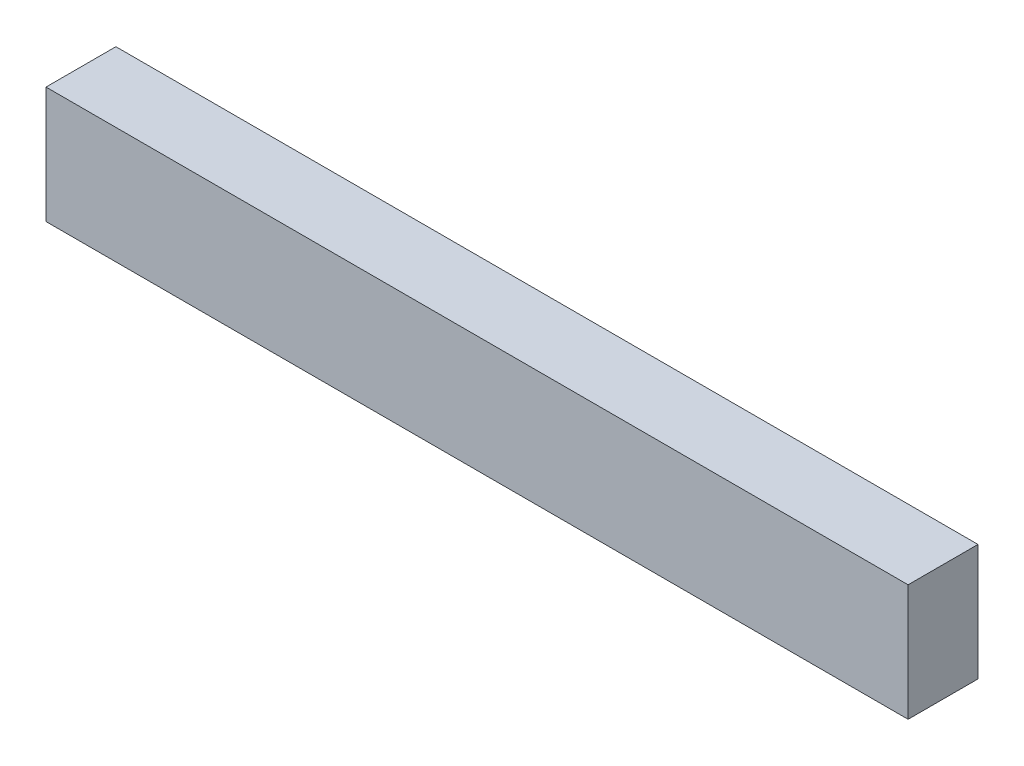
SolidWorks part; units mm, degrees
material "Pine"
ref_plane "Front Plane" through (0, 0, 0) normal (0, 0, 1) x (1, 0, 0)
ref_plane "Top Plane" through (0, 0, 0) normal (0, 1, 0) x (1, 0, 0)
ref_plane "Right Plane" through (0, 0, 0) normal (1, 0, 0) x (0, 0, -1)
sketch "Sketch1" plane through (0, 0, 0) normal (0, 1, 0) x (1, 0, 0)
  line L1 (-117.475, -9.525) -> (117.475, -9.525)
  line L2 (-117.475, -9.525) -> (-117.475, 9.525)
  line L3 (-117.475, 9.525) -> (117.475, 9.525)
  line L4 (117.475, -9.525) -> (117.475, 9.525)
  line L5 (-117.475, -9.525) -> (117.475, 9.525) construction
  line L6 (-117.475, 9.525) -> (117.475, -9.525) construction
  point P0 (0, 0)
  dimension "D1" = 19.05
  dimension "D2" = 234.95
extrude "Boss-Extrude1" add sketch "Sketch1" along normal blind 31.75
